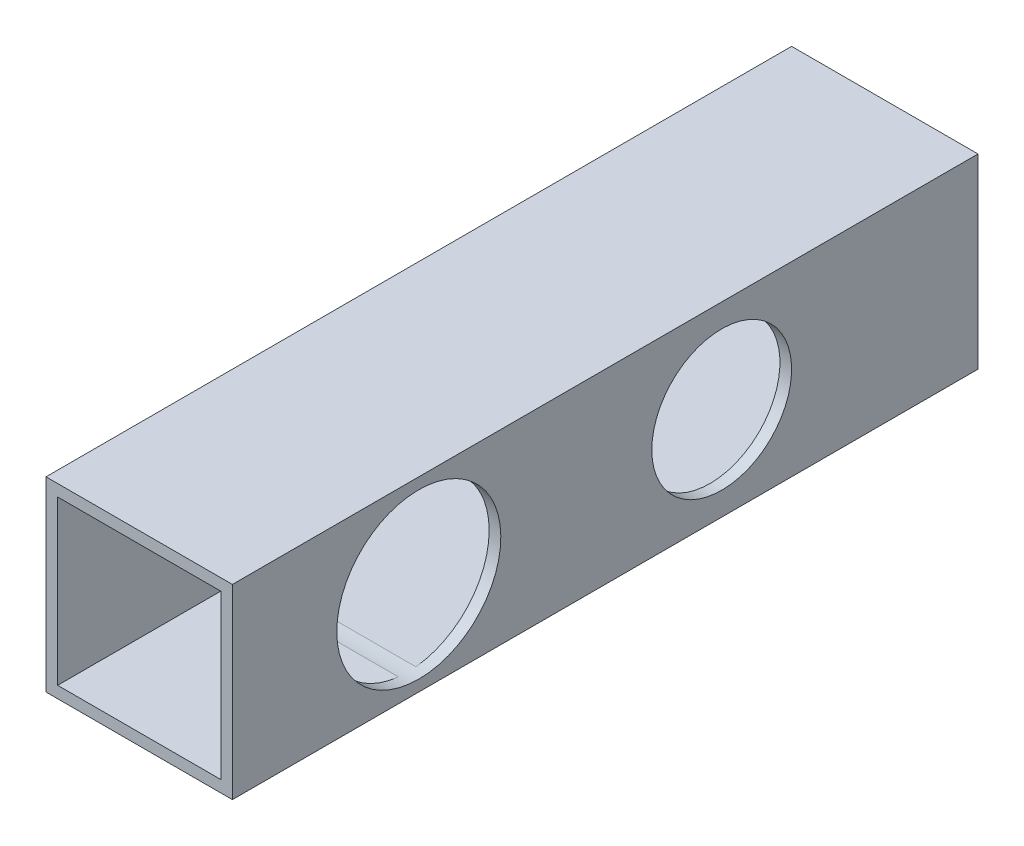
SolidWorks part; units mm, degrees
ref_plane "Front Plane" through (0, 0, 0) normal (0, 0, 1) x (1, 0, 0)
ref_plane "Top Plane" through (0, 0, 0) normal (0, 1, 0) x (1, 0, 0)
ref_plane "Right Plane" through (0, 0, 0) normal (1, 0, 0) x (0, 0, -1)
sketch "Sketch1" plane through (0, 0, 0) normal (0, 0, 1) x (1, 0, 0)
  line L0 (12.7, 0) -> (11.1125, 0) construction
  line L1 (-12.7, 0) -> (12.7, 0) construction
  line L2 (0, 12.7) -> (0, -12.7)
  point P7 (0, 0)
sketch "Sketch2" plane through (0, 0, 0) normal (1, 0, 0) x (0, 0, -1)
  line L0 (914.4, 0) -> (-914.4, 0)
  point P4 (0, 0)
  dimension "Length" = 1828.8
sketch "Sketch3" plane through (0, 0, 0) normal (0, 0, 1) x (1, 0, 0)
  line L5 (-12.7, -12.7) -> (12.7, -12.7)
  line L11 (-12.7, -12.7) -> (-12.7, 12.7)
  line L12 (-12.7, 12.7) -> (12.7, 12.7)
  line L13 (-11.1125, -11.1125) -> (11.1125, -11.1125)
  line L14 (12.7, -12.7) -> (12.7, 12.7)
  line L18 (-12.7, -12.7) -> (12.7, 12.7) construction
  line L19 (-12.7, 12.7) -> (12.7, -12.7) construction
  line L20 (-11.1125, -11.1125) -> (-11.1125, 11.1125)
  line L21 (-11.1125, 11.1125) -> (11.1125, 11.1125)
  line L22 (11.1125, -11.1125) -> (11.1125, 11.1125)
  line L23 (-11.1125, -11.1125) -> (11.1125, 11.1125) construction
  line L24 (-11.1125, 11.1125) -> (11.1125, -11.1125) construction
  point P0 (0, 0)
  point P1 (0, 0)
  point P10 (11.1125, -12.7)
  dimension "D2" = 1.5875
  dimension "D3" = 25.4
  dimension "D4" = 25.4
  dimension "D1" = 1.5875
extrude "Boss-Extrude1" add sketch "Sketch3" along normal up to vertex (914.4 mm away) and the other way up to vertex (914.4 mm away) up to point (0, 0, 914.4) other way up to point (0, 0, -914.4)
sketch "Sketch4" plane through (0, 0, 0) normal (1, 0, 0) x (0, 0, -1)
  line L0 (914.4, 0) -> (-914.4, 0) construction
  line L1 (-914.4, -12.7) -> (-914.4, 12.7) construction
  point P0 (-885.825, 0)
  point P6 (0, 0)
  point P8 (-876.3, 0)
  point P9 (876.3, 0)
  point P10 (885.825, 0)
  dimension "D1" = 28.575
  dimension "D2" = 38.1
  dimension "D3" = 28.575
  dimension "D4" = 38.1
sketch "Sketch5" plane through (0, 0, 914.4) normal (0, 0, 1) x (1, 0, 0)
  line L1 (-29.3775, -22.324) -> (29.3775, -22.324)
  line L2 (-29.3775, -22.324) -> (-29.3775, 22.324)
  line L3 (-29.3775, 22.324) -> (29.3775, 22.324)
  line L4 (29.3775, -22.324) -> (29.3775, 22.324)
  line L5 (-29.3775, -22.324) -> (29.3775, 22.324) construction
  line L6 (-29.3775, 22.324) -> (29.3775, -22.324) construction
  point P0 (0, 0)
extrude "Cut-Extrude1" cut sketch "Sketch5" against normal blind 1727.2
sketch "Sketch6" plane through (12.7, 0, 0) normal (1, 0, 0) x (0, 0, -1)
  line L1 (914.4, -12.7) -> (914.4, 12.7) construction
  circle A0 centre (879.475, 0) radius 9.525
  circle A1 centre (838.2, 0) radius 11.176
  dimension "D1" = 19.05
  dimension "D4" = 22.352
  dimension "D2" = 34.925
  dimension "D3" = 76.2
extrude "Cut-Extrude2" cut sketch "Sketch6" against normal up to surface and the other way through all up to face at (-11.1125, 0, -863.6)
sketch "Sketch9" plane through (-11.1125, 0, 0) normal (1, 0, 0) x (0, 0, -1)
  circle A0 centre (879.475, 0) radius 3.175
  circle A1 centre (879.475, 0) radius 9.525 construction
  point P2 (0, 0)
  point P3 (0, 0)
  dimension "D1" = 6.35
extrude "Cut-Extrude3" cut sketch "Sketch9" against normal through all both and the other way through all
equation "\"D2@Sketch3\"=\"Wall Thickness@Sketch1\""
equation "\"D1@Sketch4\"=\"Width@Sketch1\"*1.125"
equation "\"D2@Sketch4\"=\"Width@Sketch1\"*1.5"
equation "\"D3@Sketch4\"=\"D1@Sketch4\""
equation "\"D4@Sketch4\"=\"D2@Sketch4\""
